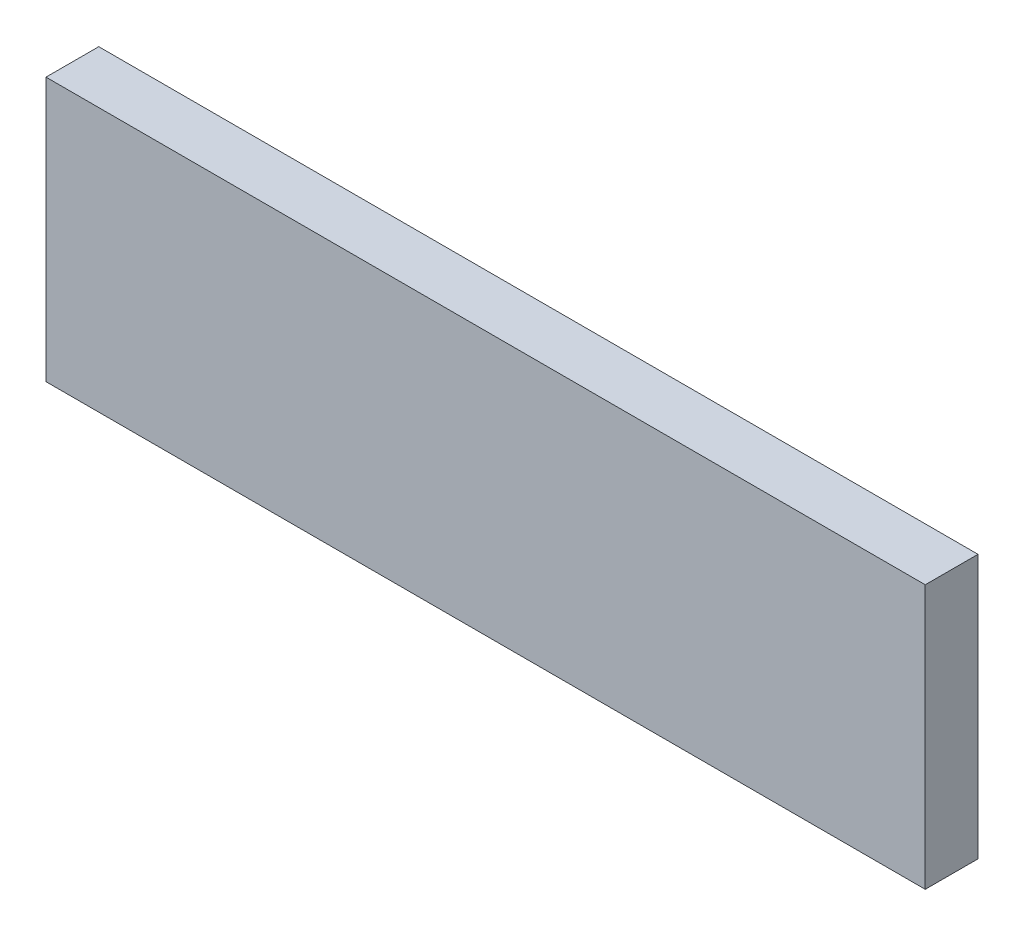
SolidWorks part; units mm, degrees
material "Polyurethane Foam Rigid"
ref_plane "Front Plane" through (0, 0, 0) normal (0, 0, 1) x (1, 0, 0)
ref_plane "Top Plane" through (0, 0, 0) normal (0, 1, 0) x (1, 0, 0)
ref_plane "Right Plane" through (0, 0, 0) normal (1, 0, 0) x (0, 0, -1)
sketch "Sketch1" plane through (0, 0, 0) normal (0, 0, 1) x (1, 0, 0)
  line L1 (0, 0) -> (50, 0)
  line L2 (0, 0) -> (0, 15)
  line L3 (0, 15) -> (50, 15)
  line L4 (50, 0) -> (50, 15)
  dimension "D1" = 15
  dimension "D2" = 50
extrude "Boss-Extrude1" add sketch "Sketch1" along normal blind 3
